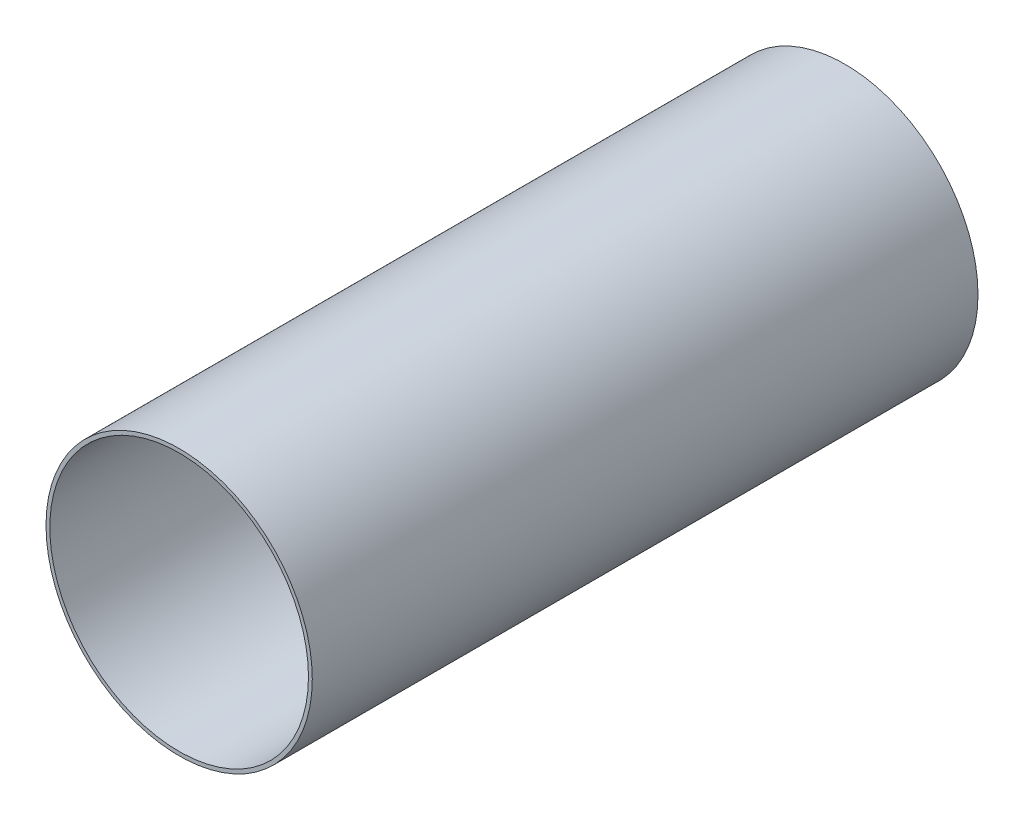
SolidWorks part; units mm, degrees
ref_plane "Front Plane" through (0, 0, 0) normal (0, 0, 1) x (1, 0, 0)
ref_plane "Top Plane" through (0, 0, 0) normal (0, 1, 0) x (1, 0, 0)
ref_plane "Right Plane" through (0, 0, 0) normal (1, 0, 0) x (0, 0, -1)
sketch "Sketch1" plane through (0, 0, 0) normal (0, 0, 1) x (1, 0, 0)
  circle A0 centre (0, 0) radius 17.5
  circle A1 centre (0, 0) radius 17
  dimension "D1" = 35
  dimension "D2" = 34
extrude "Boss-Extrude1" add sketch "Sketch1" along normal blind 87.5
